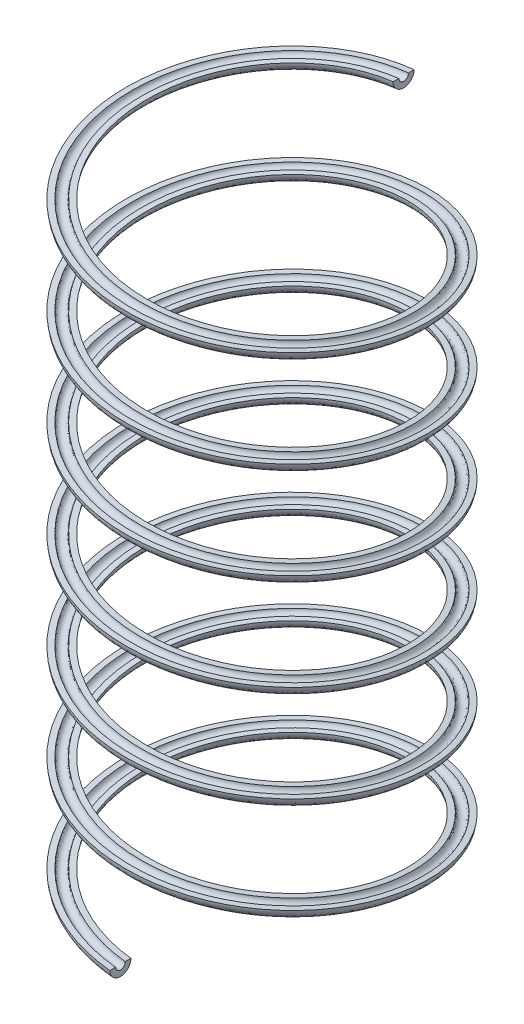
SolidWorks part; units mm, degrees
ref_plane "前基準面" through (0, 0, 0) normal (0, 0, 1) x (1, 0, 0)
ref_plane "上基準面" through (0, 0, 0) normal (0, 1, 0) x (1, 0, 0)
ref_plane "右基準面" through (0, 0, 0) normal (1, 0, 0) x (0, 0, -1)
sketch "草圖2" plane through (0, 0, 0) normal (0, 1, 0) x (1, 0, 0)
  circle A0 centre (0, 0) radius 17.5
  dimension "D1" = 35
curve "螺旋曲線/渦捲線1" pitch 11.9286 height 77.5357 turns 6.5
ref_plane "平面1" through (0, 0, 17.5) normal (0, 0, 1) x (1, 0, 0)
sketch "草圖6" plane through (0, 0, 0) normal (1, 0, 0) x (0, 0, -1)
  line L0 (16.1855, 77.5274) -> (16.8855, 77.5274)
  line L1 (18.0855, 77.5274) -> (18.7855, 77.5274)
  arc A0 (16.8855, 77.5274) -> (18.0855, 77.5274) centre (17.4855, 77.5274) ccw
  arc A1 (16.1855, 77.5274) -> (18.7855, 77.5274) centre (17.4855, 77.5274) ccw
  dimension "D1" = 1.2
  dimension "D2" = 0.7
sweep "掃出1" add profiles "草圖6" path "螺旋曲線/渦捲線1"
sketch "草圖9" plane through (0, 0, 0) normal (1, 0, 0) x (0, 0, -1)
  line L0 (17.4855, 76.2274) -> (14.2622, 0)
  arc A0 (16.1855, 77.5274) -> (18.7855, 77.5274) centre (17.4855, 77.5274) ccw construction
